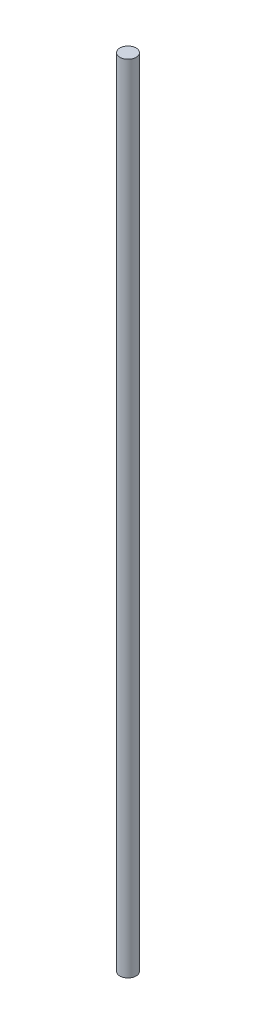
SolidWorks part; units mm, degrees
ref_plane "Front Plane" through (0, 0, 0) normal (0, 0, 1) x (1, 0, 0)
ref_plane "Top Plane" through (0, 0, 0) normal (0, 1, 0) x (1, 0, 0)
ref_plane "Right Plane" through (0, 0, 0) normal (1, 0, 0) x (0, 0, -1)
sketch "Sketch1" plane through (0, 0, 0) normal (0, 1, 0) x (1, 0, 0)
  circle A0 centre (0, 0) radius 4
  dimension "D1" = 8
extrude "Boss-Extrude1" add sketch "Sketch1" along normal blind 392 contours A0
